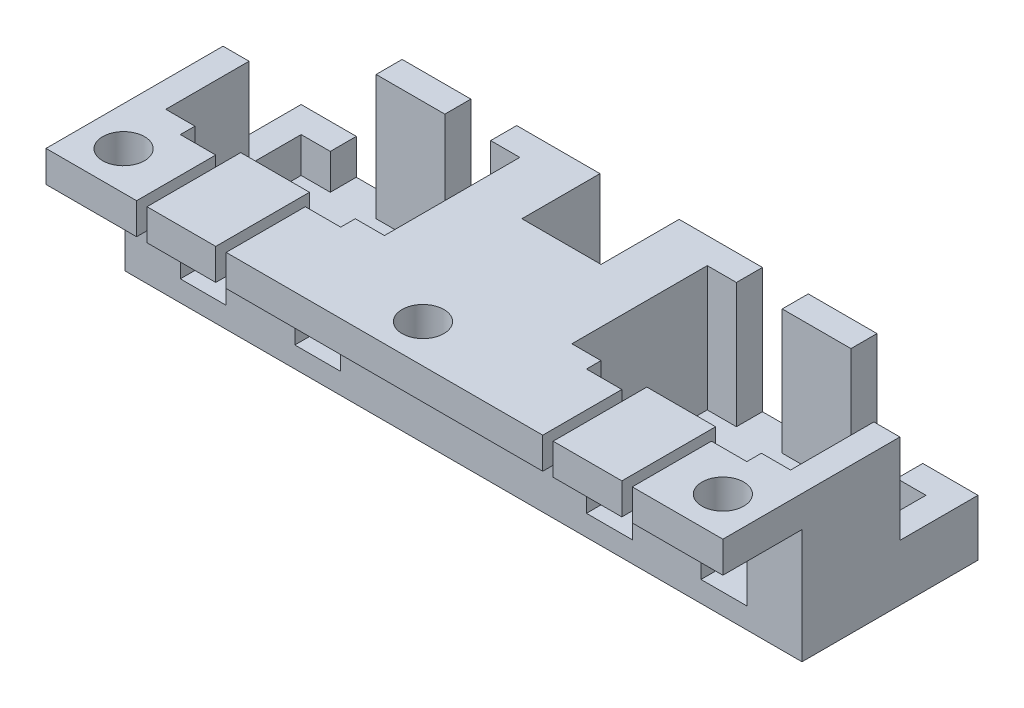
SolidWorks part; units mm, degrees
material "Delrin 2700 NC010, Low Viscosity Acetal Copolymer (SS)"
ref_plane "Front Plane" through (0, 0, 0) normal (0, 0, 1) x (1, 0, 0)
ref_plane "Top Plane" through (0, 0, 0) normal (0, 1, 0) x (1, 0, 0)
ref_plane "Right Plane" through (0, 0, 0) normal (1, 0, 0) x (0, 0, -1)
sketch "Sketch1" plane through (0, 0, 0) normal (0, 1, 0) x (1, 0, 0)
  line L0 (41.275, 5.588) -> (-41.275, 5.588)
  line L1 (-41.275, -15.875) -> (41.275, -15.875)
  line L2 (-41.275, -15.875) -> (-41.275, 5.588)
  line L4 (41.275, -15.875) -> (41.275, 5.588)
  line L5 (-41.275, -15.875) -> (41.275, 15.875) construction
  line L6 (-41.275, 15.875) -> (41.275, -15.875) construction
  point P0 (0, 0)
  dimension "D1" = 82.55
  dimension "D2" = 21.463
extrude "Plate" add sketch "Sketch1" along normal mid plane 2.54
sketch "Sketch4" plane through (0, 0, 15.875) normal (0, 0, 1) x (1, 0, 0)
  line L1 (-41.275, 1.27) -> (41.275, 1.27)
  line L2 (-41.275, 1.27) -> (-41.275, 16.51)
  line L3 (-41.275, 16.51) -> (41.275, 16.51)
  line L4 (41.275, 1.27) -> (41.275, 16.51)
  line L5 (41.275, 1.27) -> (41.275, -1.27) construction
  dimension "D1" = 15.24
  dimension "D2" = 0
extrude "Boss-Extrude1" add sketch "Sketch4" against normal blind 1.778
sketch "Sketch5" plane through (0, 0, 14.097) normal (0, 0, -1) x (-1, 0, 0)
  line L0 (41.275, 1.27) -> (-41.275, 1.27) construction
  line L1 (-41.275, 16.51) -> (-38.1, 16.51)
  line L2 (-41.275, 16.51) -> (-41.275, 1.27)
  line L3 (-41.275, 1.27) -> (-38.1, 1.27)
  line L4 (-38.1, 16.51) -> (-38.1, 1.27)
  line L6 (41.275, 16.51) -> (38.1, 16.51)
  line L7 (41.275, 16.51) -> (41.275, 1.27)
  line L8 (41.275, 1.27) -> (38.1, 1.27)
  line L9 (38.1, 16.51) -> (38.1, 1.27)
  dimension "D1" = 3.175
  dimension "D2" = 3.175
extrude "Boss-Extrude2" add sketch "Sketch5" along normal blind 19.685
sketch "Sketch9" plane through (38.1, 0, 0) normal (-1, 0, 0) x (0, 0, 1)
  line L0 (-5.588, 16.51) -> (14.097, 16.51) construction
  line L1 (-2.413, 16.51) -> (-5.588, 16.51)
  line L2 (-2.413, 16.51) -> (-2.413, 1.27)
  line L3 (-2.413, 1.27) -> (-5.588, 1.27)
  line L4 (-5.588, 16.51) -> (-5.588, 1.27)
  line L5 (-5.588, 1.27) -> (14.097, 1.27) construction
  line L6 (14.097, 1.27) -> (14.097, 16.51) construction
  dimension "D1" = 16.51
  dimension "D2" = 3.175
extrude "Boss-Extrude5" add sketch "Sketch9" along normal up to next
sketch "Sketch10" plane through (0, 0, 14.097) normal (0, 0, -1) x (-1, 0, 0)
  line L0 (38.1, 1.27) -> (-38.1, 1.27) construction
  line L1 (-8.255, 1.27) -> (-11.43, 1.27)
  line L2 (-8.255, 16.51) -> (8.255, 16.51)
  line L3 (-8.255, 16.51) -> (-11.43, 16.51)
  line L4 (-11.43, 16.51) -> (-11.43, 1.27)
  line L5 (-38.1, 16.51) -> (38.1, 16.51) construction
  line L6 (-8.255, 1.27) -> (8.255, 1.27)
  line L7 (0, 1.27) -> (0, 16.51) construction
  line L8 (11.43, 1.27) -> (11.43, 16.51)
  line L9 (8.255, 16.51) -> (11.43, 16.51)
  line L10 (-38.1, 1.27) -> (-38.1, 16.51) construction
  line L11 (8.255, 1.27) -> (11.43, 1.27)
  dimension "D1" = 26.67
  dimension "D2" = 3.175
extrude "Boss-Extrude6" add sketch "Sketch10" along normal up to next
sketch "Sketch11" plane through (0, 0, -5.588) normal (0, 0, -1) x (-1, 0, 0)
  line L0 (41.275, 16.51) -> (-41.275, 16.51) construction
  line L1 (-34.544, 16.51) -> (-28.956, 16.51)
  line L2 (-34.544, 16.51) -> (-34.544, 1.27)
  line L3 (-34.544, 1.27) -> (-28.956, 1.27)
  line L4 (-28.956, 16.51) -> (-28.956, 1.27)
  line L5 (38.1, 1.27) -> (-38.1, 1.27) construction
  line L7 (0, 1.27) -> (0, 16.51) construction
  line L8 (28.956, 16.51) -> (28.956, 1.27)
  line L9 (34.544, 1.27) -> (28.956, 1.27)
  line L10 (34.544, 16.51) -> (34.544, 1.27)
  line L11 (34.544, 16.51) -> (28.956, 16.51)
  line L12 (-41.275, 16.51) -> (-41.275, -1.27) construction
  line L13 (41.275, 16.51) -> (-41.275, 16.51) construction
  line L14 (-20.574, 16.51) -> (-14.986, 16.51)
  line L15 (-20.574, 16.51) -> (-20.574, 1.27)
  line L16 (-20.574, 1.27) -> (-14.986, 1.27)
  line L17 (-14.986, 16.51) -> (-14.986, 1.27)
  line L18 (14.986, 16.51) -> (14.986, 1.27)
  line L19 (20.574, 1.27) -> (14.986, 1.27)
  line L20 (20.574, 16.51) -> (20.574, 1.27)
  line L21 (20.574, 16.51) -> (14.986, 16.51)
  dimension "D1" = 6.731
  dimension "D2" = 5.588
  dimension "D3" = 15.24
  dimension "D4" = 20.701
  dimension "D5" = 5.588
extrude "Cut-Extrude1" cut sketch "Sketch11" against normal through all
sketch "Sketch13" plane through (0, 0, 15.875) normal (0, 0, 1) x (1, 0, 0)
  line L0 (41.275, 16.51) -> (41.275, -1.27) construction
  line L1 (-41.275, 16.51) -> (41.275, 16.51)
  line L2 (-41.275, 16.51) -> (-41.275, 12.7)
  line L3 (-41.275, 12.7) -> (41.275, 12.7)
  line L4 (41.275, 16.51) -> (41.275, 12.7)
  dimension "D1" = 3.81
extrude "Boss-Extrude7" add sketch "Sketch13" along normal blind 9.652
hole_wizard "#10 Clearance Hole1" positions "3DSketch1" profile "Sketch14" hole size "#10" standard "ANSI Inch" end condition through all
sketch3d "3DSketch1"
  line L0 (41.275, 16.51, -5.588) -> (41.275, 16.51, 25.527) construction
  line L1 (41.275, 16.51, 25.527) -> (-41.275, 16.51, 25.527) construction
  line L2 (-41.275, 16.51, -5.588) -> (-41.275, 16.51, 25.527) construction
  point P0 (36.5125, 16.51, 20.7645)
  point P2 (0, 16.51, 20.828)
  point P4 (-36.5125, 16.51, 20.828)
  dimension "D1" = 4.7625
  dimension "D2" = 4.7625
  dimension "D3" = 41.275
  dimension "D4" = 4.7625
  dimension "D5" = 4.699
  dimension "D6" = 4.699
sketch "Sketch14" plane through (36.5125, 16.51, 20.7645) normal (1, 0, 0) x (0, 0, 1)
  line L0 (0, 0) -> (0, 17.78)
  line L1 (0, 17.78) -> (2.5527, 17.78)
  line L2 (2.5527, 17.78) -> (2.5527, 0)
  line L5 (2.5527, 0) -> (0, 0)
  line L11 (0, -6.35) -> (0, 107.95) construction
  dimension "Thru Hole Dia." = 5.1054
  dimension "Thru Hole Depth" = 17.78
sketch "Sketch16" plane through (0, 0, -5.588) normal (0, 0, -1) x (-1, 0, 0)
  line L0 (0, 16.51) -> (0, -1.27) construction
  line L1 (-41.275, 16.51) -> (-34.29, 16.51)
  line L2 (-41.275, 16.51) -> (-41.275, 5.588)
  line L3 (-41.275, 5.588) -> (-34.29, 5.588)
  line L4 (-34.29, 16.51) -> (-34.29, 5.588)
  line L5 (28.956, 16.51) -> (20.574, 16.51) construction
  line L6 (-41.275, -1.27) -> (41.275, -1.27) construction
  line L7 (34.29, 16.51) -> (34.29, 5.588)
  line L8 (41.275, 5.588) -> (34.29, 5.588)
  line L9 (41.275, 16.51) -> (41.275, 5.588)
  line L10 (41.275, 16.51) -> (34.29, 16.51)
  line L12 (-4.826, 16.51) -> (4.826, 16.51)
  line L13 (-4.826, 16.51) -> (-4.826, 5.588)
  line L14 (-4.826, 5.588) -> (4.826, 5.588)
  line L15 (4.826, 16.51) -> (4.826, 5.588)
  dimension "D1" = 10.922
  dimension "D2" = 6.985
  dimension "D3" = 9.652
  dimension "D4" = 10.922
  dimension "D5" = 4.826
extrude "Cut-Extrude4" cut sketch "Sketch16" against normal blind 9.525
sketch "Sketch18" plane through (0, 16.51, 0) normal (0, 1, 0) x (1, 0, 0)
  line L0 (41.275, -25.527) -> (-41.275, -25.527) construction
  line L1 (-28.956, -15.875) -> (-30.226, -15.875)
  line L2 (-28.956, -15.875) -> (-28.956, -25.527)
  line L3 (-28.956, -25.527) -> (-30.226, -25.527)
  line L4 (-30.226, -15.875) -> (-30.226, -25.527)
  line L6 (-20.574, -15.875) -> (-19.304, -15.875)
  line L7 (-20.574, -15.875) -> (-20.574, -25.527)
  line L8 (-20.574, -25.527) -> (-19.304, -25.527)
  line L9 (-19.304, -15.875) -> (-19.304, -25.527)
  line L11 (0, -25.527) -> (0, 1.5768) construction
  line L12 (19.304, -15.875) -> (19.304, -25.527)
  line L13 (20.574, -25.527) -> (19.304, -25.527)
  line L14 (20.574, -15.875) -> (20.574, -25.527)
  line L15 (20.574, -15.875) -> (19.304, -15.875)
  line L16 (30.226, -15.875) -> (30.226, -25.527)
  line L17 (28.956, -25.527) -> (30.226, -25.527)
  line L18 (28.956, -15.875) -> (28.956, -25.527)
  line L19 (28.956, -15.875) -> (30.226, -15.875)
  dimension "D1" = 1.27
  dimension "D2" = 1.27
extrude "Cut-Extrude6" cut sketch "Sketch18" against normal through all
